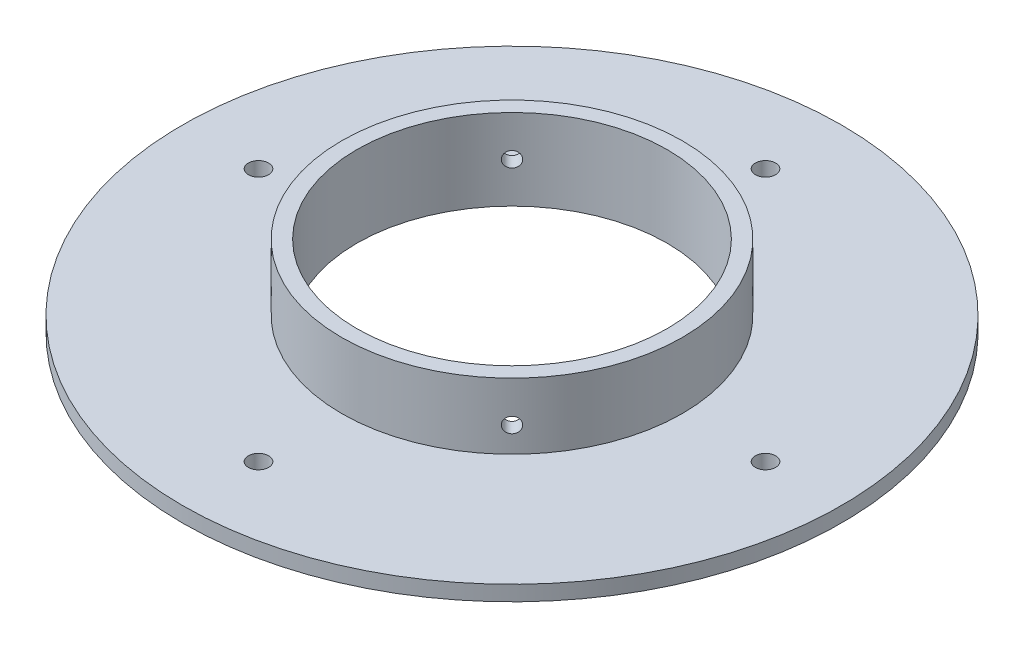
SolidWorks part; units mm, degrees
ref_plane "Front Plane" through (0, 0, 0) normal (0, 0, 1) x (1, 0, 0)
ref_plane "Top Plane" through (0, 0, 0) normal (0, 1, 0) x (1, 0, 0)
ref_plane "Right Plane" through (0, 0, 0) normal (1, 0, 0) x (0, 0, -1)
sketch "Sketch2" plane through (0, 0, 0) normal (0, 0, 1) x (1, 0, 0)
  line L0 (0, 31.8685) -> (0, -33.6468) construction
  line L1 (30.6, 16) -> (30.6, 0)
  line L2 (30.6, 0) -> (65, 0)
  line L3 (65, 0) -> (65, 3)
  line L4 (65, 3) -> (33.6, 3)
  line L5 (33.6, 3) -> (33.6, 16)
  line L6 (33.6, 16) -> (30.6, 16)
  dimension "D1" = 33.6
  dimension "D2" = 3
  dimension "D3" = 65
  dimension "D4" = 3
  dimension "D5" = 16
revolve "Revolve1" add sketch "Sketch2" angle 360 about L0
sketch "Sketch3" plane through (0, 3, 0) normal (0, 1, 0) x (1, 0, 0)
  line L0 (0, 69.3575) -> (0, -68.2374) construction
  line L1 (-78.2256, 0) -> (81.2127, 0) construction
  circle A0 centre (0, 50) radius 2
  circle A1 centre (50, 0) radius 2
  circle A2 centre (0, -50) radius 2
  circle A3 centre (-50, 0) radius 2
  point P7 (49.433, 13.1771)
  point P8 (0, 0)
  point P9 (0, 0)
  point P16 (0, 0)
  dimension "D1" = 4
  dimension "D2" = 50
  dimension "D3" = 4
extrude "Cut-Extrude1" cut sketch "Sketch3" against normal through all
sketch "Sketch4" plane through (0, 0, 0) normal (0, 0, 1) x (1, 0, 0)
  line L0 (0, 0) -> (0, 58.4206) construction
ref_plane "Plane1" through (0, 0, 0) normal (0.7071, 0, 0.7071) x (0, 1, 0)
sketch "Sketch5" plane through (0, 0, 0) normal (0.7071, 0, 0.7071) x (0, 1, 0)
  line L0 (0, 0) -> (16, 0) construction
  line L1 (16, -33.6) -> (16, 33.6) construction
  line L2 (0, 65) -> (0, -65) construction
  circle A0 centre (8, 0) radius 1.5
  dimension "D1" = 3
extrude "Cut-Extrude2" cut sketch "Sketch5" against normal through all
pattern_circular "CirPattern1" count 4 every 90 about axis through (0, 31.8685, 0) along (0, 1, 0) of "Cut-Extrude2"
